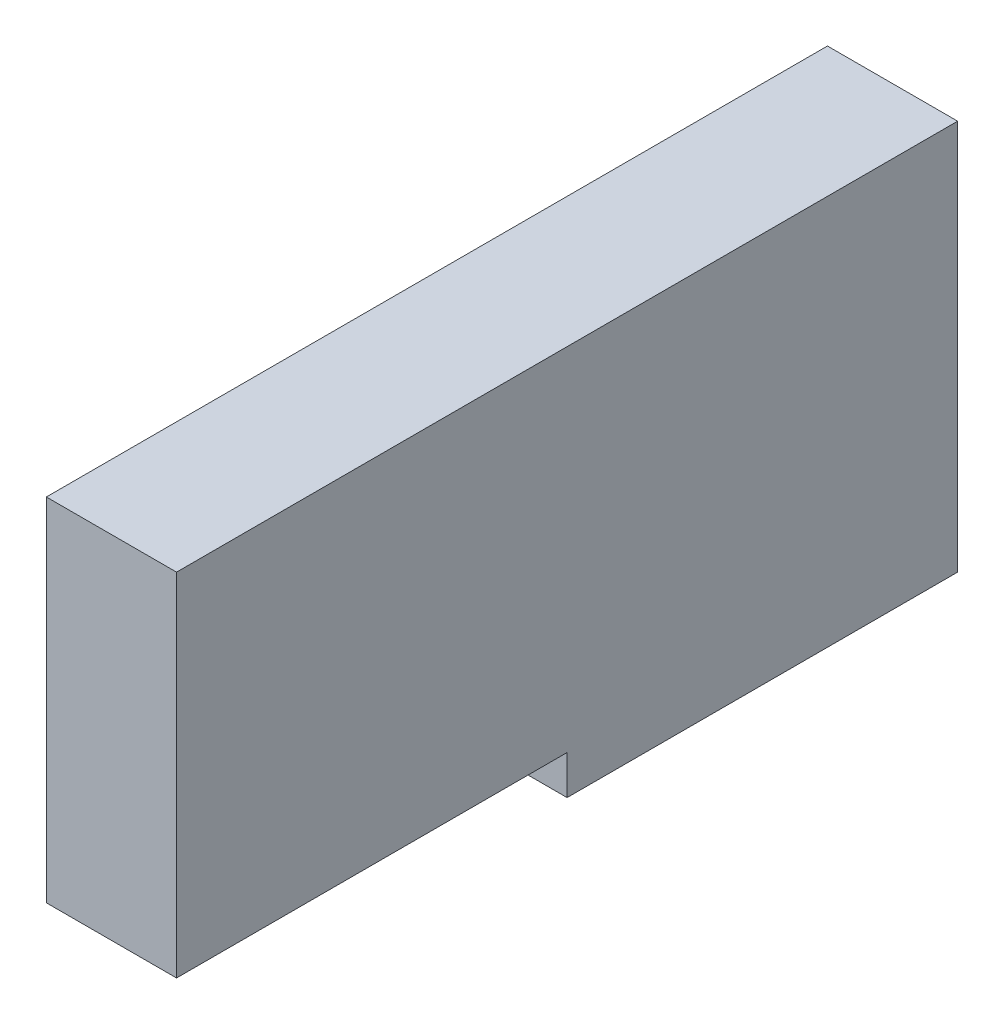
SolidWorks part; units mm, degrees
ref_plane "Plan de face" through (0, 0, 0) normal (0, 0, 1) x (1, 0, 0)
ref_plane "Plan de dessus" through (0, 0, 0) normal (0, 1, 0) x (1, 0, 0)
ref_plane "Plan de droite" through (0, 0, 0) normal (1, 0, 0) x (0, 0, -1)
sketch "Esquisse1" plane through (0, 0, 0) normal (0, 0, 1) x (1, 0, 0)
  line L0 (5, 30) -> (5, 0) construction
  line L1 (0, 0) -> (10, 0)
  line L2 (0, 0) -> (0, 30)
  line L3 (0, 30) -> (10, 30)
  line L4 (10, 0) -> (10, 30)
  circle A0 centre (5, 5) radius 1.75
  circle A1 centre (5, 15) radius 1.75
  circle A2 centre (5, 25) radius 1.75
  point P13 (0, 0)
  dimension "D3" = 3.5
  dimension "D4" = 5
  dimension "D1" = 10
  dimension "D2" = 30
  dimension "D5" = 10
  dimension "D6" = 10
extrude "Boss.-Extru.1" add sketch "Esquisse1" along normal blind 20
sketch "Esquisse2" plane through (0, 0, 20) normal (0, 0, 1) x (1, 0, 0)
  line L1 (0, 0) -> (10, 0)
  line L2 (0, 0) -> (0, 30)
  line L3 (0, 30) -> (10, 30)
  line L4 (10, 0) -> (10, 30)
extrude "Boss.-Extru.2" add sketch "Esquisse2" along normal blind 10
sketch "Esquisse3" plane through (0, 0, 30) normal (0, 0, 1) x (1, 0, 0)
  line L0 (10, 0) -> (10, 30) construction
  line L1 (0, 30) -> (10, 30)
  line L2 (0, 30) -> (0, 3)
  line L3 (0, 3) -> (10, 3)
  line L4 (10, 30) -> (10, 3)
  line L5 (0, 0) -> (10, 0) construction
  dimension "D1" = 3
extrude "Boss.-Extru.3" add sketch "Esquisse3" along normal blind 30
sketch "Esquisse4" plane through (0, 3, 0) normal (0, -1, 0) x (-1, 0, 0)
  line L0 (-5, -60) -> (-5, -30) construction
  line L1 (0, -60) -> (-10, -60) construction
  line L2 (0, -30) -> (-10, -30) construction
  circle A0 centre (-5, -55) radius 1.75
  circle A1 centre (-5, -45) radius 1.75
  circle A2 centre (-5, -35) radius 1.75
  point P12 (0, 0)
  point P13 (0, 0)
  dimension "D1" = 3.5
  dimension "D2" = 10
  dimension "D3" = 10
  dimension "D4" = 5
extrude "Enlèv. mat.-Extru.1" cut sketch "Esquisse4" against normal blind 15
